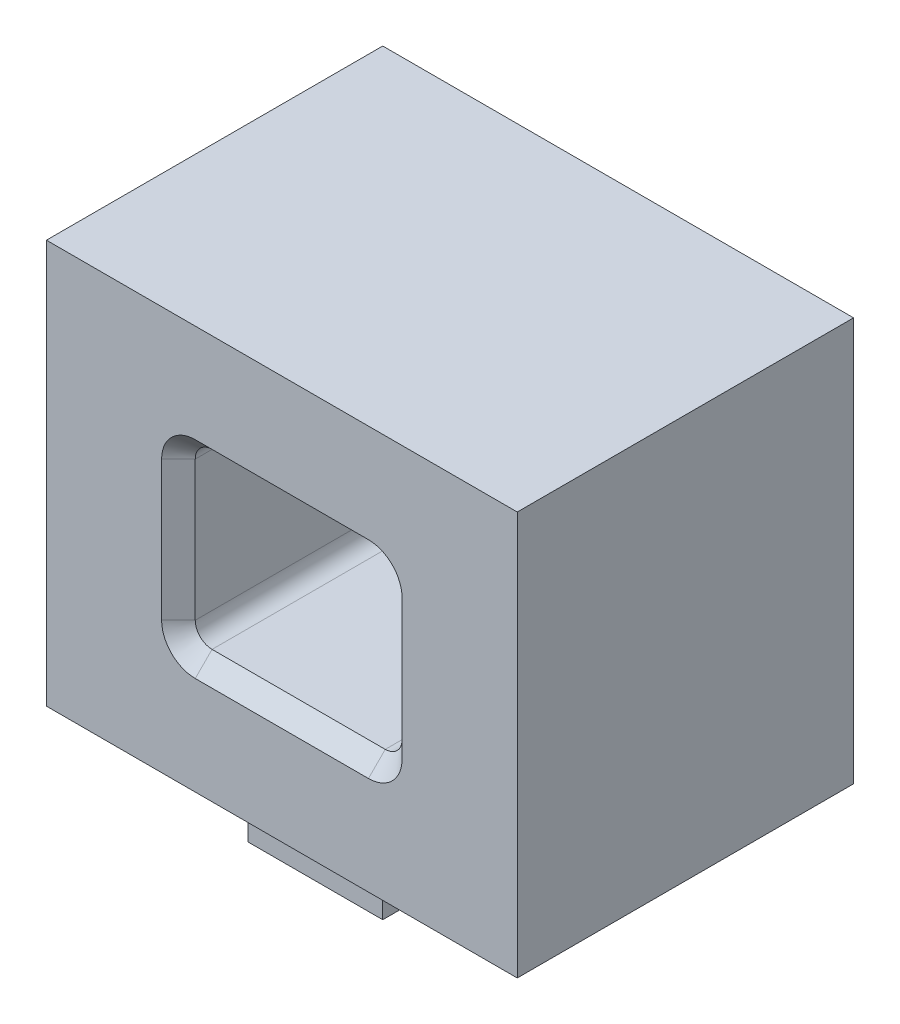
SolidWorks part; units mm, degrees
ref_plane "Front Plane" through (0, 0, 0) normal (0, 0, 1) x (1, 0, 0)
ref_plane "Top Plane" through (0, 0, 0) normal (0, 1, 0) x (1, 0, 0)
ref_plane "Right Plane" through (0, 0, 0) normal (1, 0, 0) x (0, 0, -1)
sketch "Sketch1" plane through (0, 0, 0) normal (0, 0, 1) x (1, 0, 0)
  line L1 (-14, -12) -> (14, -12)
  line L2 (-14, -12) -> (-14, 12)
  line L3 (-14, 12) -> (14, 12)
  line L4 (14, -12) -> (14, 12)
  line L5 (-14, -12) -> (14, 12) construction
  line L6 (-14, 12) -> (14, -12) construction
  point P0 (0, 0)
  dimension "D1" = 28
  dimension "D2" = 24
extrude "Boss-Extrude1" add sketch "Sketch1" along normal blind 20
sketch "Sketch2" plane through (0, 0, 20) normal (0, 0, 1) x (1, 0, 0)
  line L1 (-6.15, -5.15) -> (6.15, -5.15)
  line L2 (-6.15, -5.15) -> (-6.15, 5.15)
  line L3 (-6.15, 5.15) -> (6.15, 5.15)
  line L4 (6.15, -5.15) -> (6.15, 5.15)
  line L5 (-6.15, -5.15) -> (6.15, 5.15) construction
  line L6 (-6.15, 5.15) -> (6.15, -5.15) construction
  point P0 (0, 0)
  dimension "D1" = 12.3
  dimension "D2" = 10.3
extrude "Cut-Extrude1" cut sketch "Sketch2" against normal blind 15.3 contours L2 L1 L4 L3
sketch "Sketch3" plane through (0, -12, 0) normal (0, -1, 0) x (1, 0, 0)
  line L0 (0, 20) -> (0, 0) construction
  line L1 (-14, 20) -> (14, 20) construction
  line L2 (-14, 10) -> (14, 10) construction
  line L3 (-14, 20) -> (-14, 0) construction
  line L4 (14, 20) -> (14, 0) construction
  line L5 (-4, 2) -> (4, 2)
  line L6 (-4, 12) -> (4, 12)
  line L7 (-4, 12) -> (-4, 18)
  line L8 (-4, 18) -> (4, 18)
  line L9 (4, 12) -> (4, 18)
  line L10 (-4, 12) -> (4, 18) construction
  line L11 (-4, 18) -> (4, 12) construction
  line L12 (4, 8) -> (4, 2)
  line L13 (-4, 8) -> (4, 8)
  line L14 (-4, 8) -> (-4, 2)
  circle A0 centre (0, 15) radius 1.7
  circle A1 centre (0, 5) radius 1.7
  point P11 (0, 15)
  dimension "D4" = 3.4
  dimension "D1" = 6
  dimension "D2" = 8
  dimension "D3" = 2
extrude "Boss-Extrude3" add sketch "Sketch3" along normal blind 3
fillet "Fillet1" radius 1 4 edges at (6.15, -5.15, 12.35) (6.15, 5.15, 12.35) (-6.15, 5.15, 12.35) (-6.15, -5.15, 12.35)
chamfer "Chamfer1" distance 1 angle 45 8 edges at (0, 5.15, 20) (-5.8571, 4.8571, 20) (5.8571, 4.8571, 20) (-6.15, 0, 20) (6.15, 0, 20) (-5.8571, -4.8571, 20) (5.8571, -4.8571, 20) (0, -5.15, 20)
fillet "Fillet2" radius 1 8 edges at (-4, -12, 5) (0, -12, 8) (0, -12, 2) (4, -12, 5) (4, -12, 15) (0, -12, 12) (-4, -12, 15) (0, -12, 18)
